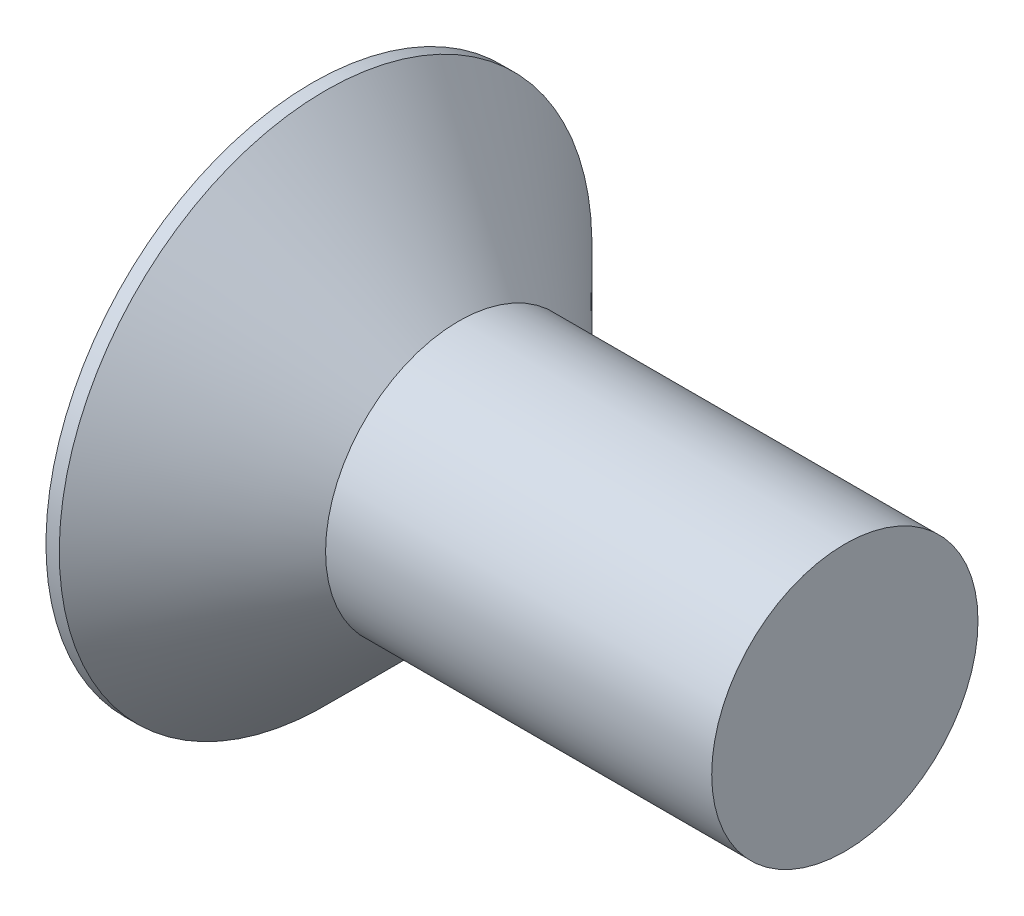
SolidWorks part; units mm, degrees
material "Plain Carbon Steel"
ref_plane "Front Plane" through (0, 0, 0) normal (0, 0, 1) x (1, 0, 0)
ref_plane "Top Plane" through (0, 0, 0) normal (0, 1, 0) x (1, 0, 0)
ref_plane "Right Plane" through (0, 0, 0) normal (1, 0, 0) x (0, 0, -1)
sketch "Sketch1" plane through (0, 0, 0) normal (0, 0, 1) x (1, 0, 0)
  line L0 (0, 0) -> (0, 10)
  line L1 (0, 10) -> (0.5, 10)
  line L2 (0.5, 10) -> (5.5, 5)
  line L3 (5.5, 5) -> (20, 5)
  line L4 (20, 5) -> (20, 0)
  line L5 (20, 0) -> (0, 0) construction
  line L6 (0, 0) -> (20, 0)
  dimension "D1" = 45
  dimension "D2" = 10
  dimension "D3" = 20
  dimension "D4" = 5.5
  dimension "D5" = 20
revolve "Revolve1" add sketch "Sketch1" angle 360 about L5
sketch "Sketch2" plane through (0, 0, 0) normal (-1, 0, 0) x (0, 0, 1)
  line L1 (1.7321, 3) -> (-1.7321, 3)
  line L2 (-1.7321, 3) -> (-3.4641, 0)
  line L3 (-3.4641, 0) -> (-1.7321, -3)
  line L4 (-1.7321, -3) -> (1.7321, -3)
  line L5 (1.7321, -3) -> (3.4641, 0)
  line L6 (3.4641, 0) -> (1.7321, 3)
  circle A1 centre (0, 0) radius 3 construction
  dimension "D1" = 6
extrude "Cut-Extrude1" cut sketch "Sketch2" against normal blind 4.4
